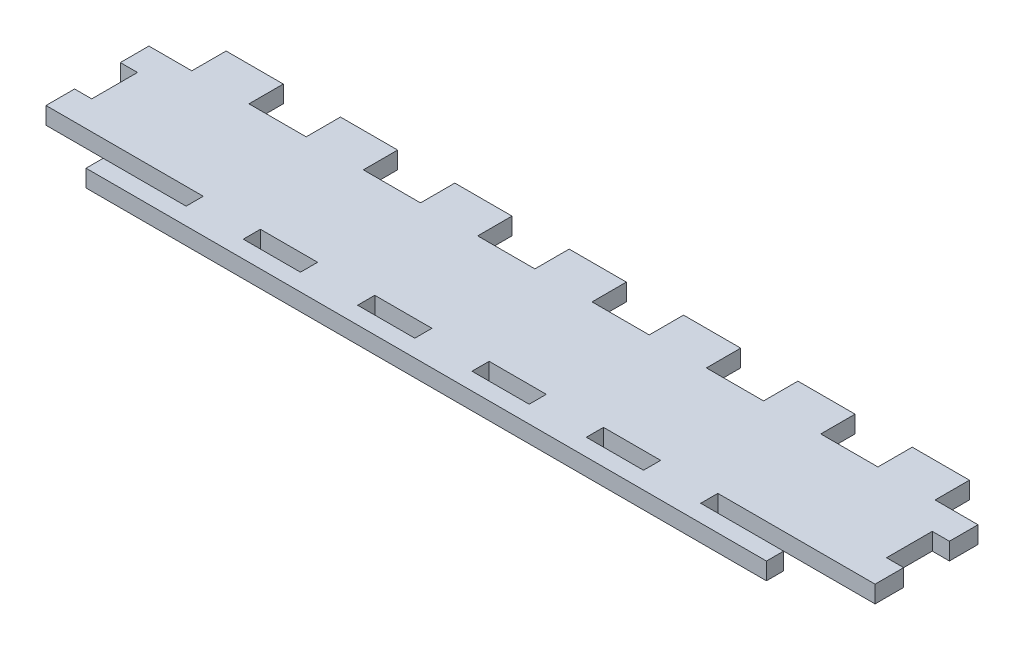
SolidWorks part; units mm, degrees
material "Maple"
ref_plane "Front Plane" through (0, 0, 0) normal (0, 0, 1) x (1, 0, 0)
ref_plane "Top Plane" through (0, 0, 0) normal (0, 1, 0) x (1, 0, 0)
ref_plane "Right Plane" through (0, 0, 0) normal (1, 0, 0) x (0, 0, -1)
sketch "Sketch1" plane through (0, 0, 0) normal (0, 1, 0) x (1, 0, 0)
  line L1 (0, 0) -> (145, 0)
  line L2 (0, 0) -> (0, -18)
  line L3 (0, -18) -> (145, -18)
  line L4 (145, 0) -> (145, -18)
  dimension "D1" = 145
  dimension "D2" = 18
extrude "Boss-Extrude1" add sketch "Sketch1" along normal blind 3
sketch "Sketch2" plane through (0, 0, 0) normal (0, -1, 0) x (1, 0, 0)
  line L0 (72.5, 18) -> (72.5, 0) construction
  line L1 (0, 18) -> (145, 18) construction
  line L2 (145, 0) -> (0, 0) construction
  line L4 (67.5, 21) -> (77.5, 21)
  line L5 (67.5, 21) -> (67.5, 18)
  line L6 (67.5, 18) -> (77.5, 18)
  line L7 (77.5, 21) -> (77.5, 18)
  line L8 (67.5, 21) -> (77.5, 18) construction
  line L9 (67.5, 18) -> (77.5, 21) construction
  line L10 (67.5, 0) -> (77.5, 0)
  line L11 (67.5, 0) -> (67.5, -6)
  line L12 (67.5, -6) -> (77.5, -6)
  line L13 (77.5, 0) -> (77.5, -6)
  line L14 (67.5, 0) -> (77.5, -6) construction
  line L15 (67.5, -6) -> (77.5, 0) construction
  point P6 (72.5, 19.5)
  point P11 (72.5, -3)
  dimension "D1" = 10
  dimension "D2" = 3
  dimension "D3" = 6
extrude "Boss-Extrude2" add sketch "Sketch2" against normal through all
pattern_linear "LPattern1" count 4 spacing 20 along (1, 0, 0) count 4 spacing 20 along (-1, 0, 0) of "Boss-Extrude2"
sketch "Sketch3" plane through (0, 3, 0) normal (0, 1, 0) x (1, 0, 0)
  line L0 (57.5, -21) -> (47.5, -21) construction
  line L1 (0, -21) -> (145, -21)
  line L2 (0, -21) -> (0, -24)
  line L3 (0, -24) -> (145, -24)
  line L4 (145, -21) -> (145, -24)
  line L5 (0, 0) -> (0, -18) construction
  line L6 (145, -18) -> (145, 0) construction
  dimension "D1" = 3
extrude "Boss-Extrude3" add sketch "Sketch3" against normal through all
sketch "Sketch4" plane through (0, 3, 0) normal (0, 1, 0) x (1, 0, 0)
  line L9 (7.5, -18) -> (17.5, -18)
  line L10 (7.5, -18) -> (7.5, -21)
  line L11 (7.5, -21) -> (17.5, -21)
  line L12 (17.5, -18) -> (17.5, -21)
  line L13 (137.5, -18) -> (127.5, -18)
  line L14 (137.5, -18) -> (137.5, -21)
  line L15 (137.5, -21) -> (127.5, -21)
  line L16 (127.5, -18) -> (127.5, -21)
extrude "Cut-Extrude1" cut sketch "Sketch4" against normal through all
sketch "Sketch5" plane through (0, 3, 0) normal (0, 1, 0) x (1, 0, 0)
  line L0 (27.5, -21) -> (0, -21) construction
  line L1 (0, -24) -> (13, -24)
  line L2 (0, -24) -> (0, -21)
  line L3 (0, -21) -> (13, -21)
  line L4 (13, -24) -> (13, -21)
  line L5 (145, -21) -> (117.5, -21) construction
  line L6 (145, -24) -> (132, -24)
  line L7 (145, -24) -> (145, -21)
  line L8 (145, -21) -> (132, -21)
  line L9 (132, -24) -> (132, -21)
  dimension "D1" = 13
extrude "Cut-Extrude2" cut sketch "Sketch5" against normal through all
sketch "Sketch6" plane through (0, 0, 0) normal (0, -1, 0) x (1, 0, 0)
  line L0 (0, 0) -> (0, 18) construction
  line L1 (3, 13) -> (0, 13)
  line L2 (3, 13) -> (3, 5)
  line L3 (3, 5) -> (0, 5)
  line L4 (0, 13) -> (0, 5)
  line L10 (145, 18) -> (145, 0) construction
  line L11 (142, 13) -> (145, 13)
  line L12 (142, 13) -> (142, 5)
  line L13 (142, 5) -> (145, 5)
  line L14 (145, 13) -> (145, 5)
  line L20 (0, 18) -> (27.5, 18) construction
  line L21 (7.5, 0) -> (0, 0) construction
  dimension "D1" = 5
  dimension "D2" = 3
  dimension "D3" = 5
extrude "Cut-Extrude3" cut sketch "Sketch6" against normal through all
